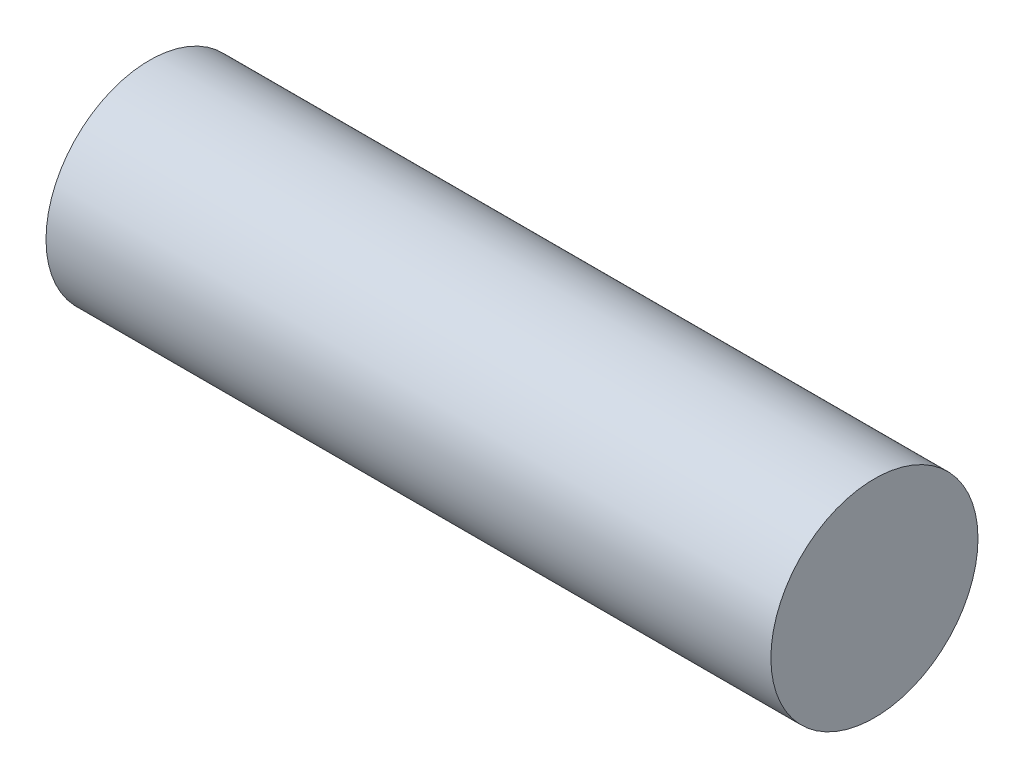
SolidWorks part; units mm, degrees
ref_plane "Front Plane" through (0, 0, 0) normal (0, 0, 1) x (1, 0, 0)
ref_plane "Top Plane" through (0, 0, 0) normal (0, 1, 0) x (1, 0, 0)
ref_plane "Right Plane" through (0, 0, 0) normal (1, 0, 0) x (0, 0, -1)
sketch "Sketch1" plane through (0, 0, 0) normal (1, 0, 0) x (0, 0, -1)
  circle A0 centre (0, 0) radius 10
  dimension "20" = 20
extrude "Boss-Extrude1" add sketch "Sketch1" along normal blind 70
